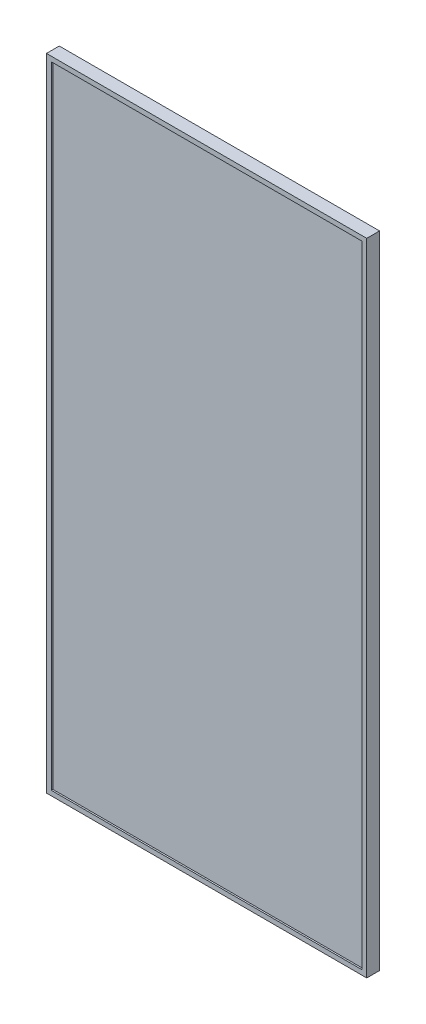
SolidWorks part; units mm, degrees
ref_plane "Alzado" through (0, 0, 0) normal (0, 0, 1) x (1, 0, 0)
ref_plane "Planta" through (0, 0, 0) normal (0, 1, 0) x (1, 0, 0)
ref_plane "Vista lateral" through (0, 0, 0) normal (1, 0, 0) x (0, 0, -1)
sketch "Croquis1" plane through (0, 0, 0) normal (0, 0, 1) x (1, 0, 0)
  line L1 (500, 1000) -> (-500, 1000)
  line L2 (500, 1000) -> (500, -1000)
  line L3 (500, -1000) -> (-500, -1000)
  line L4 (-500, 1000) -> (-500, -1000)
  line L5 (500, 1000) -> (-500, -1000) construction
  line L6 (500, -1000) -> (-500, 1000) construction
  point P0 (0, 0)
  dimension "D1" = 2000
  dimension "D2" = 1000
extrude "Saliente-Extruir2" add sketch "Croquis1" along normal blind 40
sketch "Croquis2" plane through (0, 0, 0) normal (0, 0, -1) x (-1, 0, 0)
  line L0 (-500, 1000) -> (500, 1000) construction
  line L1 (470, -970) -> (-470, -970)
  line L2 (470, -970) -> (470, 970)
  line L3 (470, 970) -> (-470, 970)
  line L4 (-470, -970) -> (-470, 970)
  line L5 (470, -970) -> (-470, 970) construction
  line L6 (470, 970) -> (-470, -970) construction
  line L7 (-500, -1000) -> (-500, 1000) construction
  point P0 (0, 0)
  dimension "D1" = 30
  dimension "D2" = 30
extrude "Cortar-Extruir1" cut sketch "Croquis2" against normal blind 30
sketch "Croquis3" plane through (0, 0, 0) normal (1, 0, 0) x (0, 0, -1)
  line L0 (-5, -995) -> (-5, 995)
  line L1 (-5, -995) -> (-30, -995)
  line L2 (-5, 995) -> (-30, 995)
  line L3 (-30, -995) -> (-30, 995)
  line L4 (-40, 1000) -> (-40, -1000) construction
  line L5 (-40, 1000) -> (0, 1000) construction
  line L6 (0, 1000) -> (0, -1000) construction
  line L7 (-40, -1000) -> (0, -1000) construction
  dimension "D1" = 10
  dimension "D2" = 5
  dimension "D3" = 5
  dimension "D4" = 5
extrude "Cortar-Extruir2" cut sketch "Croquis3" against normal blind 495 and the other way blind 495
sketch "Croquis4" plane through (0, 0, 40) normal (0, 0, 1) x (1, 0, 0)
  line L0 (500, 1000) -> (-500, 1000) construction
  line L1 (-485, -985) -> (485, -985)
  line L2 (-485, -985) -> (-485, 985)
  line L3 (-485, 985) -> (485, 985)
  line L4 (485, -985) -> (485, 985)
  line L5 (-485, -985) -> (485, 985) construction
  line L6 (-485, 985) -> (485, -985) construction
  line L7 (500, -1000) -> (500, 1000) construction
  point P0 (0, 0)
  dimension "D1" = 15
  dimension "D2" = 15
extrude "Cortar-Extruir3" cut sketch "Croquis4" against normal blind 5
